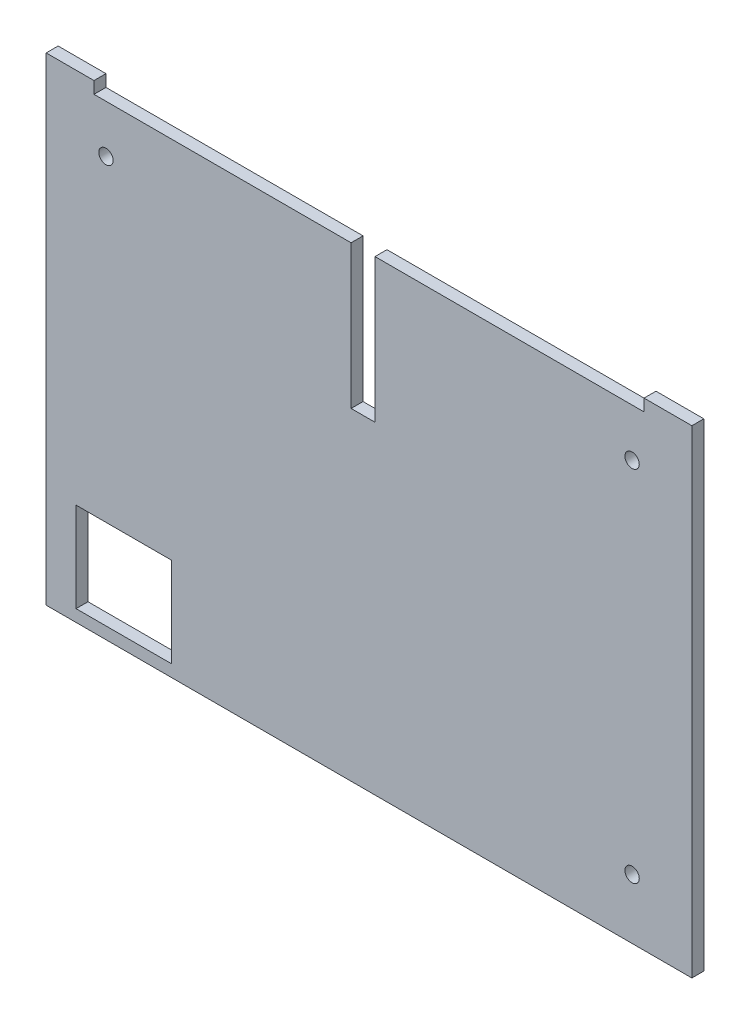
SolidWorks part; units mm, degrees
ref_plane "Plan de face" through (0, 0, 0) normal (0, 0, 1) x (1, 0, 0)
ref_plane "Plan de dessus" through (0, 0, 0) normal (0, 1, 0) x (1, 0, 0)
ref_plane "Plan de droite" through (0, 0, 0) normal (1, 0, 0) x (0, 0, -1)
sketch "Esquisse1" plane through (0, 0, 0) normal (0, 0, 1) x (1, 0, 0)
  line L1 (-135, 100) -> (135, 100)
  line L2 (-135, 100) -> (-135, -100)
  line L3 (-135, -100) -> (135, -100)
  line L4 (135, 100) -> (135, -100)
  line L5 (-135, 100) -> (135, -100) construction
  line L6 (-135, -100) -> (135, 100) construction
  line L7 (-135, 22.5) -> (-90, 22.5)
  line L8 (-135, 22.5) -> (-135, -22.5)
  line L9 (-135, -22.5) -> (-90, -22.5)
  line L10 (-90, 22.5) -> (-90, -22.5)
  point P0 (0, 0)
  point P10 (-90, 0)
  dimension "D1" = 270
  dimension "D2" = 200
  dimension "D3" = 100
  dimension "D4" = 45
  dimension "D5" = 45
extrude "Boss.-Extru.2" add sketch "Esquisse1" along normal blind 5 contours L7 L10 L9 L2 L3 L4 L1
sketch "Esquisse2" plane through (0, 0, 5) normal (0, 0, 1) x (1, 0, 0)
  line L0 (-135, -100) -> (135, -100) construction
  line L1 (135, 100) -> (135, -100) construction
  circle A0 centre (110, -75) radius 3
  dimension "D1" = 6
  dimension "D2" = 25
  dimension "D3" = 25
extrude "Enlèv. mat.-Extru.1" cut sketch "Esquisse2" against normal through all
ref_plane "Plan1" through (0, 0, 0) normal (1, 0, 0) x (0, 0, -1)
mirror "Symétrie1" about plane through (0, 0, 0) normal (1, 0, 0) of "Enlèv. mat.-Extru.1"
ref_plane "Plan2" through (0, 0, 0) normal (0, -1, 0) x (-1, 0, 0)
mirror "Symétrie2" about plane through (0, 0, 0) normal (0, -1, 0) of "Symétrie1", "Enlèv. mat.-Extru.1"
sketch "Esquisse4" plane through (0, 0, 5) normal (0, 0, 1) x (1, 0, 0)
  line L0 (135, -95) -> (-135, -95) construction
  line L1 (-82.5, -95) -> (-122.5, -95)
  line L2 (-82.5, -95) -> (-82.5, -57.5)
  line L3 (-82.5, -57.5) -> (-122.5, -57.5)
  line L4 (-122.5, -95) -> (-122.5, -57.5)
  line L5 (-82.5, -57.5) -> (-82.5, -97.5) construction
extrude "Enlèv. mat.-Extru.2" cut sketch "Esquisse4" against normal blind 60
sketch "Esquisse5" plane through (0, -22.5, 0) normal (0, 1, 0) x (1, 0, 0)
  line L1 (-90, -5) -> (-135, -5)
  line L2 (-90, -5) -> (-90, 0)
  line L3 (-90, 0) -> (-135, 0)
  line L4 (-135, -5) -> (-135, 0)
extrude "Boss.-Extru.3" add sketch "Esquisse5" along normal blind 60
sketch "Esquisse7" plane through (0, 100, 0) normal (0, 1, 0) x (1, 0, 0)
  line L0 (-135, 0) -> (135, 0) construction
  line L1 (-115, 0) -> (115, 0)
  line L2 (-115, 0) -> (-115, -5)
  line L3 (-115, -5) -> (115, -5)
  line L4 (115, 0) -> (115, -5)
  line L5 (-135, -5) -> (135, -5) construction
  line L6 (-135, -5) -> (-135, 0) construction
  line L7 (135, -5) -> (135, 0) construction
  point P10 (-135, -2.5)
  point P13 (135, -2.5)
  dimension "D1" = 20
  dimension "D2" = 20
extrude "Enlèv. mat.-Extru.3" cut sketch "Esquisse7" against normal blind 5
sketch "Esquisse11" plane through (0, 0, 0) normal (0, 0, -1) x (-1, 0, 0)
  line L0 (-115, 95) -> (115, 95) construction
  line L1 (-7.5, 95) -> (7.5, 95)
  line L2 (-7.5, 95) -> (-7.5, 35)
  line L3 (-7.5, 35) -> (7.5, 35)
  line L4 (7.5, 95) -> (7.5, 35)
  line L5 (0, 2.75) -> (0, -2.75) construction
  point P6 (0, 95)
  dimension "D1" = 0
  dimension "D2" = 15
  dimension "D3" = 60
extrude "Enlèv. mat.-Extru.4" cut sketch "Esquisse11" against normal blind 10
sketch "Esquisse12" plane through (7.5, 0, 0) normal (-1, 0, 0) x (0, 0, 1)
  line L1 (0, 95) -> (5, 95)
  line L2 (0, 95) -> (0, 35)
  line L3 (0, 35) -> (5, 35)
  line L4 (5, 95) -> (5, 35)
extrude "Boss.-Extru.4" add sketch "Esquisse12" along normal blind 5
sketch "Esquisse13" plane through (0, 0, 5) normal (0, 0, 1) x (1, 0, 0)
  line L12 (115, 95) -> (2.5, 95)
  line L13 (2.5, 95) -> (2.5, 35)
  line L14 (2.5, 35) -> (-7.5, 35)
  line L15 (-7.5, 35) -> (-7.5, 95)
  line L16 (-7.5, 95) -> (-115, 95)
  line L17 (-115, 95) -> (-115, 100)
  line L18 (-115, 100) -> (-135, 100)
  line L19 (-135, 100) -> (-135, -100)
  line L20 (-135, -100) -> (135, -100)
  line L21 (135, -100) -> (135, 100)
  line L22 (135, 100) -> (115, 100)
  line L23 (115, 100) -> (115, 95)
  line L24 (115, 95) -> (2.5, 95)
  line L25 (2.5, 95) -> (2.5, 35)
  line L26 (2.5, 35) -> (-7.5, 35)
  line L27 (-7.5, 35) -> (-7.5, 95)
  line L28 (-7.5, 95) -> (-115, 95)
  line L29 (-115, 95) -> (-115, 100)
  line L30 (-115, 100) -> (-135, 100)
  line L31 (-135, 100) -> (-135, -100)
  line L32 (-135, -100) -> (135, -100)
  line L33 (135, -100) -> (135, 100)
  line L34 (135, 100) -> (115, 100)
  line L35 (115, 100) -> (115, 95)
  dimension "D1" = 0
